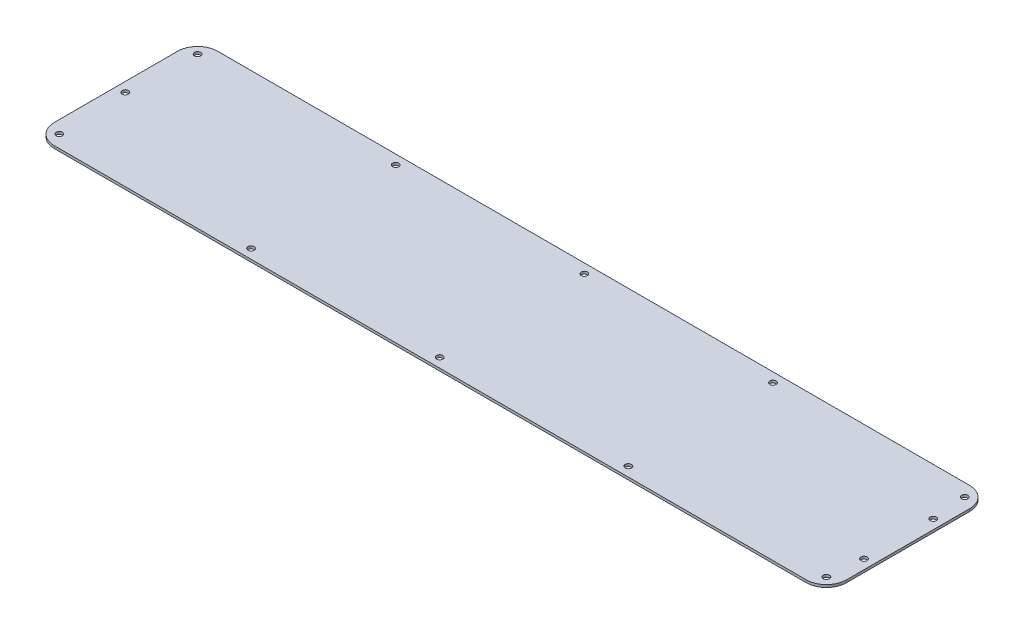
SolidWorks part; units mm, degrees
material "Acrylic (Medium-high impact)"
ref_plane "Front Plane" through (0, 0, 0) normal (0, 0, 1) x (1, 0, 0)
ref_plane "Top Plane" through (0, 0, 0) normal (0, 1, 0) x (1, 0, 0)
ref_plane "Right Plane" through (0, 0, 0) normal (1, 0, 0) x (0, 0, -1)
sketch "Sketch1" plane through (0, 0, 0) normal (0, 1, 0) x (1, 0, 0)
  line L1 (-315, 65) -> (315, 65)
  line L2 (-315, 65) -> (-315, -65)
  line L3 (-315, -65) -> (315, -65)
  line L4 (315, 65) -> (315, -65)
  line L5 (-315, 65) -> (315, -65) construction
  line L6 (-315, -65) -> (315, 65) construction
  point P0 (0, 0)
  dimension "D1" = 630
  dimension "D2" = 130
extrude "Boss-Extrude1" add sketch "Sketch1" along normal blind 2
fillet "Fillet1" radius 16 4 edges at (-315, 1, -65) (315, 1, -65) (315, 1, 65) (-315, 1, 65)
sketch "Sketch2" plane through (0, 2, 0) normal (0, 1, 0) x (1, 0, 0)
  line L20 (299, 57.5) -> (-299, 57.5)
  line L21 (307.5, -49) -> (307.5, 49)
  line L22 (-299, -57.5) -> (299, -57.5)
  line L23 (-307.5, 49) -> (-307.5, -49)
  line L24 (299, 57.5) -> (-299, 57.5)
  line L25 (307.5, -49) -> (307.5, 49)
  line L26 (-299, -57.5) -> (299, -57.5)
  line L27 (-307.5, 49) -> (-307.5, -49)
  arc A24 (307.5, 49) -> (299, 57.5) centre (299, 49) ccw
  arc A25 (299, -57.5) -> (307.5, -49) centre (299, -49) ccw
  arc A26 (-307.5, -49) -> (-299, -57.5) centre (-299, -49) ccw
  arc A27 (-299, 57.5) -> (-307.5, 49) centre (-299, 49) ccw
  arc A28 (307.5, 49) -> (299, 57.5) centre (299, 49) ccw
  arc A29 (299, -57.5) -> (307.5, -49) centre (299, -49) ccw
  arc A30 (-307.5, -49) -> (-299, -57.5) centre (-299, -49) ccw
  arc A31 (-299, 57.5) -> (-307.5, 49) centre (-299, 49) ccw
  point P0 (-305.0104, 55.0104)
  point P1 (0, 57.5)
  point P2 (0, -57.5)
  point P3 (-305.0104, -55.0104)
  point P4 (305.0104, -55.0104)
  point P5 (305.0104, 55.0104)
  point P6 (150, 57.5)
  point P7 (-150, 57.5)
  point P8 (-307.5, 0)
  point P9 (307.5, 0)
  point P10 (150, -57.5)
  point P12 (-150, -57.5)
  point P24 (307.5, 27.5)
  point P25 (307.5, -27.5)
  dimension "D6" = 30
  dimension "D2" = 150
  dimension "D3" = 150
  dimension "D4" = 150
  dimension "D5" = 150
  dimension "D7" = 30
  dimension "D1" = 7.5
hole_wizard "Ø5.0 (5) Diameter Hole1" positions "3DSketch1" profile "Sketch3" hole size "Ø5.0" standard "DIN" end condition through all
sketch3d "3DSketch1"
  point P0 (-305.0104, 2, -55.0104)
  point P3 (-150, 2, -57.5)
  point P6 (-307.5, 2, 0)
  point P9 (-305.0104, 2, 55.0104)
  point P12 (-150, 2, 57.5)
  point P15 (0, 2, -57.5)
  point P18 (0, 2, 57.5)
  point P21 (150, 2, 57.5)
  point P24 (150, 2, -57.5)
  point P27 (305.0104, 2, -55.0104)
  point P33 (305.0104, 2, 55.0104)
  point P36 (307.5, 2, -27.5)
  point P39 (307.5, 2, 27.5)
sketch "Sketch3" plane through (-305.0104, 2, -55.0104) normal (1, 0, 0) x (0, 0, 1)
  line L0 (0, 0) -> (0, 2)
  line L1 (0, 2) -> (2.5, 2)
  line L2 (2.5, 2) -> (2.5, 0)
  line L5 (2.5, 0) -> (0, 0)
  line L11 (0, -6.35) -> (0, 107.95) construction
  dimension "Thru Hole Dia." = 5
  dimension "Thru Hole Depth" = 2
